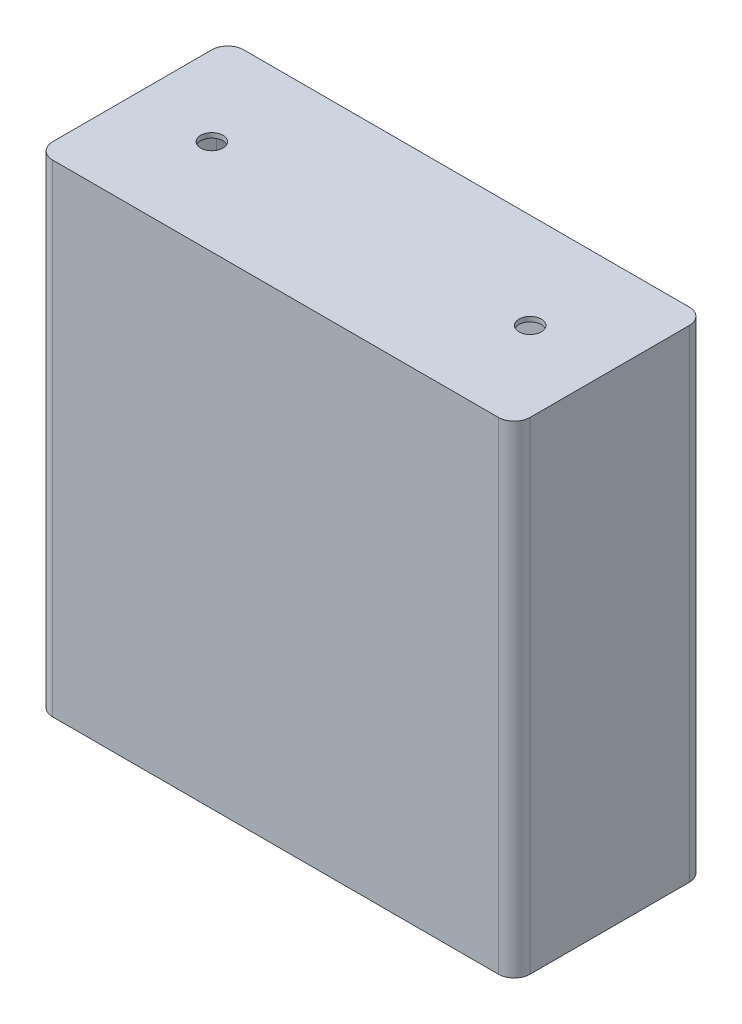
SolidWorks part; units mm, degrees
material "6061 Alloy"
ref_plane "Front Plane" through (0, 0, 0) normal (0, 0, 1) x (1, 0, 0)
ref_plane "Top Plane" through (0, 0, 0) normal (0, 1, 0) x (1, 0, 0)
ref_plane "Right Plane" through (0, 0, 0) normal (1, 0, 0) x (0, 0, -1)
sketch "Sketch2" plane through (0, 0, 0) normal (0, 1, 0) x (1, 0, 0)
  line L0 (0, 60) -> (300, 60) construction
  line L1 (10, 0) -> (290, 0)
  line L2 (0, 10) -> (0, 110)
  line L3 (10, 120) -> (290, 120)
  line L4 (300, 10) -> (300, 110)
  line L5 (150, 60) -> (150, 120) construction
  arc A0 (290, 120) -> (300, 110) centre (290, 110) cw
  arc A1 (300, 10) -> (290, 0) centre (290, 10) cw
  arc A2 (0, 10) -> (10, 0) centre (10, 10) ccw
  arc A3 (0, 110) -> (10, 120) centre (10, 110) cw
  point P7 (300, 120)
  point P12 (0, 0)
  point P15 (0, 120)
  dimension "D3" = 10
  dimension "D1" = 120
  dimension "D2" = 300
extrude "Boss-Extrude1" add sketch "Sketch2" along normal blind 300
shell "Shell5" thickness 3
sketch "Sketch3" plane through (0, 300, 0) normal (0, 1, 0) x (1, 0, 0)
  line L0 (290, 120) -> (10, 120) construction
  line L1 (10, 0) -> (290, 0)
  line L2 (0, 10) -> (0, 110)
  line L3 (10, 120) -> (290, 120)
  line L4 (300, 10) -> (300, 110)
  line L5 (300, 10) -> (300, 110) construction
  arc A0 (300, 110) -> (290, 120) centre (290, 110) ccw
  arc A1 (300, 10) -> (290, 0) centre (290, 10) cw
  arc A2 (0, 10) -> (10, 0) centre (10, 10) ccw
  arc A3 (0, 110) -> (10, 120) centre (10, 110) cw
  point P15 (0, 0)
  dimension "D1" = 10
extrude "Boss-Extrude2" add sketch "Sketch3" along normal blind 3
sketch "Sketch4" plane through (0, 303, 0) normal (0, 1, 0) x (1, 0, 0)
  line L0 (0, 60) -> (300, 60) construction
  line L1 (0, 110) -> (0, 10) construction
  line L2 (300, 10) -> (300, 110) construction
  line L3 (150, 120) -> (150, 0) construction
  line L4 (290, 120) -> (10, 120) construction
  line L5 (10, 0) -> (290, 0) construction
  circle A0 centre (50, 60) radius 7
  circle A1 centre (250, 60) radius 7
  dimension "D1" = 14
  dimension "D2" = 50
extrude "Cut-Extrude1" cut sketch "Sketch4" against normal through all and the other way through all
